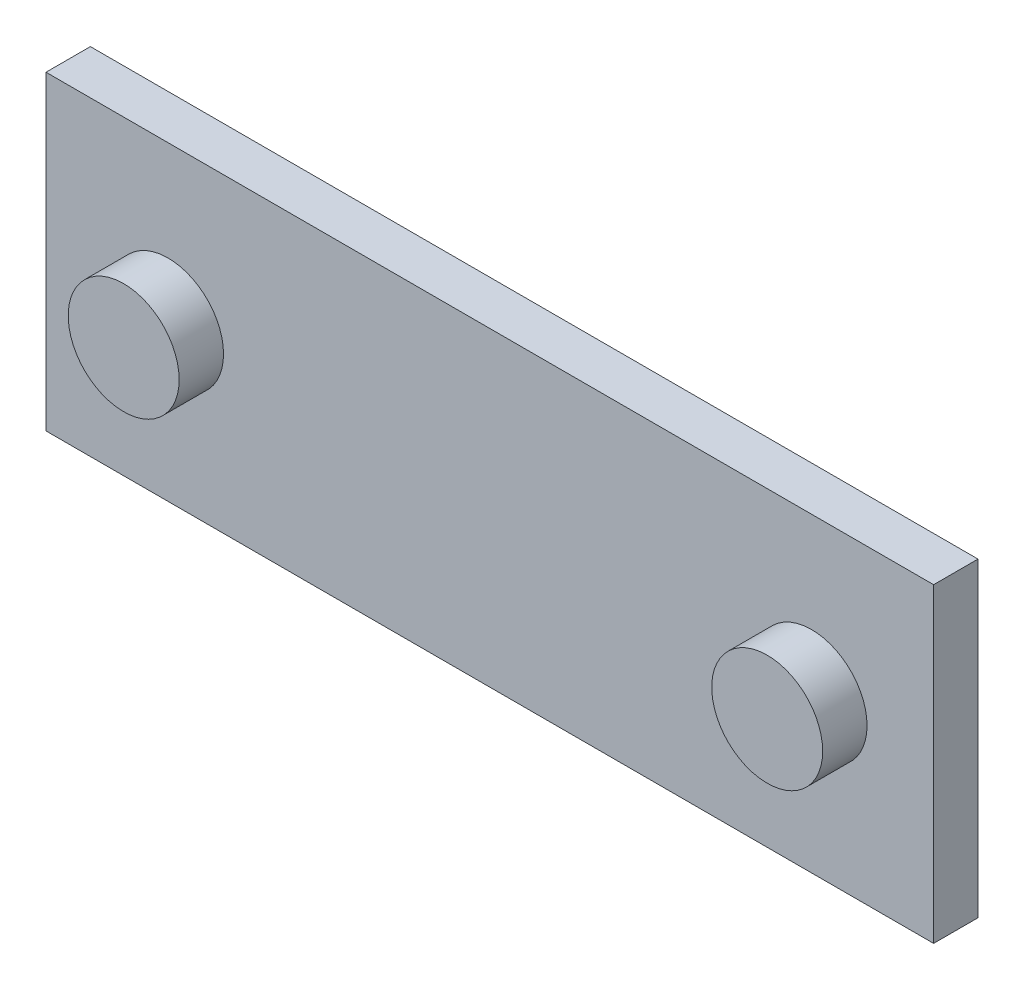
SolidWorks part; units mm, degrees
ref_plane "Front Plane" through (0, 0, 0) normal (0, 0, 1) x (1, 0, 0)
ref_plane "Top Plane" through (0, 0, 0) normal (0, 1, 0) x (1, 0, 0)
ref_plane "Right Plane" through (0, 0, 0) normal (1, 0, 0) x (0, 0, -1)
sketch "Sketch1" plane through (0, 0, 0) normal (0, 0, 1) x (1, 0, 0)
  line L1 (10, -3.5) -> (-10, -3.5)
  line L2 (10, -3.5) -> (10, 3.5)
  line L3 (10, 3.5) -> (-10, 3.5)
  line L4 (-10, -3.5) -> (-10, 3.5)
  line L5 (10, -3.5) -> (-10, 3.5) construction
  line L6 (10, 3.5) -> (-10, -3.5) construction
  point P0 (0, 0)
  dimension "D1" = 20
  dimension "D2" = 7
extrude "Boss-Extrude1" add sketch "Sketch1" along normal blind 1
sketch "Sketch2" plane through (0, 0, 1) normal (0, 0, 1) x (1, 0, 0)
  circle A0 centre (-7.25, 0) radius 1.25
  circle A1 centre (7.25, 0) radius 1.25
  dimension "D3" = 2.5
  dimension "D4" = 2.5
  dimension "D1" = 14.5
  dimension "D2" = 7.25
extrude "Boss-Extrude2" add sketch "Sketch2" along normal blind 1
